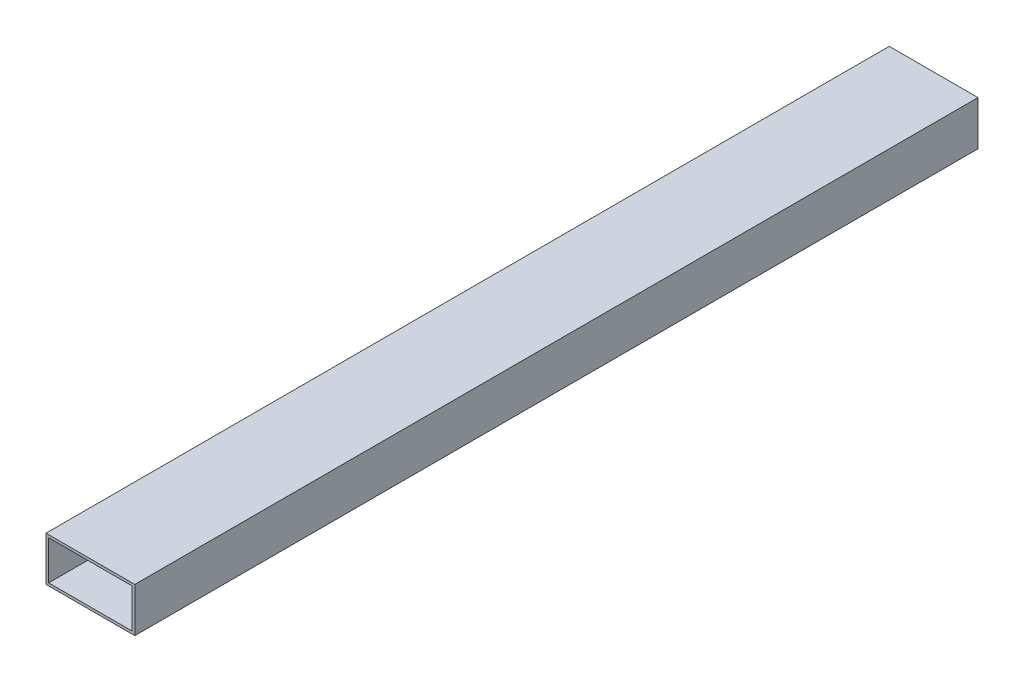
SolidWorks part; units mm, degrees
ref_plane "Front Plane" through (0, 0, 0) normal (0, 0, 1) x (1, 0, 0)
ref_plane "Top Plane" through (0, 0, 0) normal (0, 1, 0) x (1, 0, 0)
ref_plane "Right Plane" through (0, 0, 0) normal (1, 0, 0) x (0, 0, -1)
sketch "Sketch1" plane through (0, 0, 0) normal (0, 0, 1) x (1, 0, 0)
  line L1 (0, 0) -> (-50.8, 0)
  line L2 (0, 0) -> (0, 25.4)
  line L3 (0, 25.4) -> (-50.8, 25.4)
  line L4 (-50.8, 0) -> (-50.8, 25.4)
  dimension "D1" = 50.8
  dimension "D2" = 25.4
extrude "Extrude-Thin1" add sketch "Sketch1" along normal blind 482.6 thin
